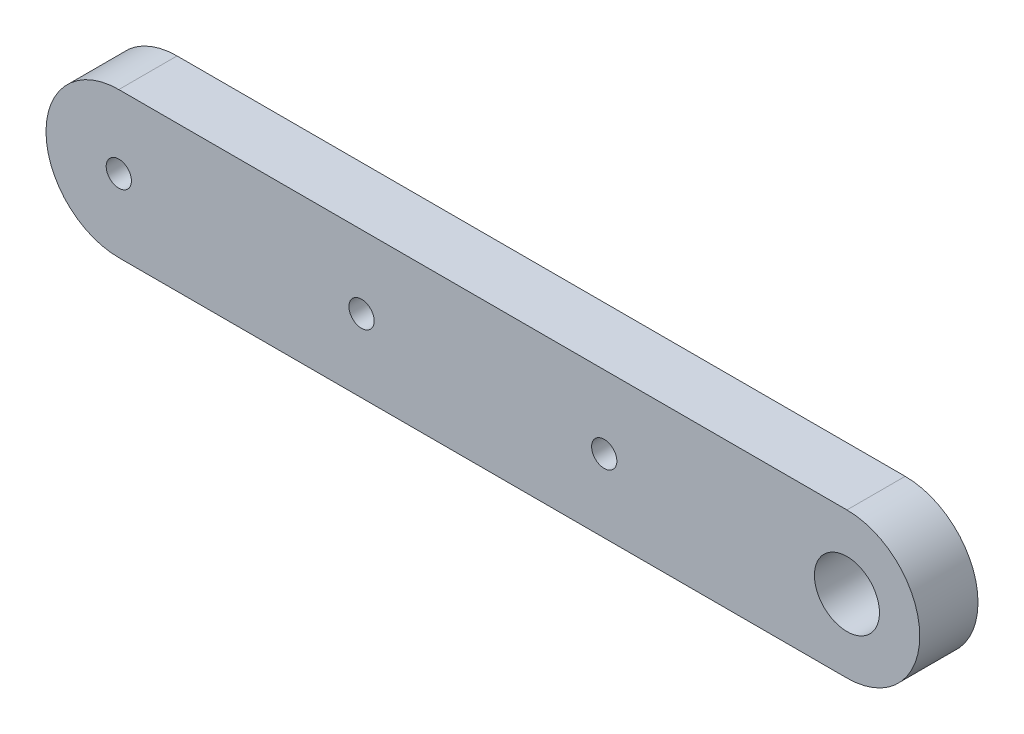
SolidWorks part; units mm, degrees
material "Pine"
ref_plane "Front Plane" through (0, 0, 0) normal (0, 0, 1) x (1, 0, 0)
ref_plane "Top Plane" through (0, 0, 0) normal (0, 1, 0) x (1, 0, 0)
ref_plane "Right Plane" through (0, 0, 0) normal (1, 0, 0) x (0, 0, -1)
sketch "Sketch1" plane through (0, 0, 0) normal (0, 0, 1) x (1, 0, 0)
  line L0 (0, 7.5) -> (75, 7.5)
  line L1 (75, -7.5) -> (0, -7.5)
  circle A0 centre (0, 0) radius 7.5
  circle A1 centre (75, 0) radius 7.5
  dimension "D1" = 75
  dimension "D2" = 15
extrude "Boss-Extrude1" add sketch "Sketch1" along normal blind 6 contours A1 L0 A0 L1 | A1 | A0
ref_plane "Plane1" through (0, 0, 3) normal (0, 0, 1) x (1, 0, 0)
sketch "Sketch2" plane through (0, 0, 6) normal (0, 0, 1) x (1, 0, 0)
  circle A0 centre (0, 0) radius 1.3
  circle A1 centre (75, 0) radius 1.3
  dimension "D1" = 2.6
extrude "Cut-Extrude1" cut sketch "Sketch2" against normal through all
pattern_linear "LPattern1" count 4 spacing 25 along (1, 0, 0) of "Cut-Extrude1"
sketch "Sketch3" plane through (0, 0, 6) normal (0, 0, 1) x (1, 0, 0)
  circle A0 centre (75, 0) radius 3.35
  dimension "D1" = 6.7
extrude "Cut-Extrude2" cut sketch "Sketch3" against normal through all
